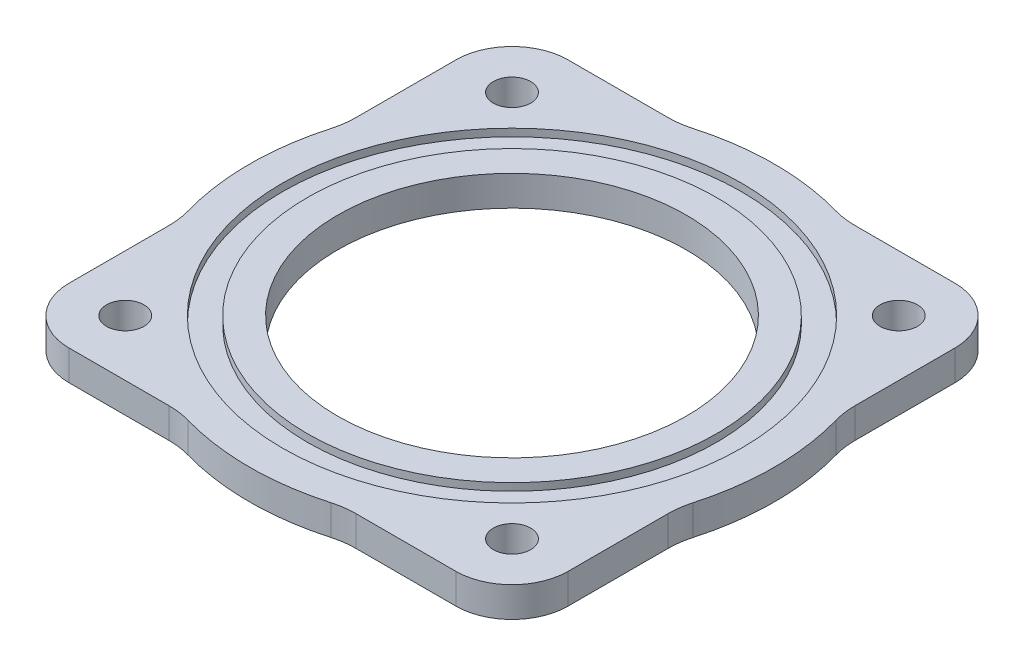
SolidWorks part; units mm, degrees
ref_plane "Front Plane" through (0, 0, 0) normal (0, 0, 1) x (1, 0, 0)
ref_plane "Top Plane" through (0, 0, 0) normal (0, 1, 0) x (1, 0, 0)
ref_plane "Right Plane" through (0, 0, 0) normal (1, 0, 0) x (0, 0, -1)
sketch "Sketch1" plane through (0, 0, 0) normal (0, 1, 0) x (1, 0, 0)
  line L0 (0, 43.6291) -> (0, 56.3563)
  line L1 (7.1437, 0) -> (19.8709, 0)
  line L2 (0, 7.1437) -> (0, 19.8709)
  line L3 (7.1437, 63.5) -> (19.8709, 63.5)
  line L4 (63.5, 7.1437) -> (63.5, 19.8709)
  line L5 (43.6291, 63.5) -> (56.3563, 63.5)
  line L6 (63.5, 43.6291) -> (63.5, 56.3563)
  line L7 (43.6291, 0) -> (56.3563, 0)
  circle A0 centre (31.75, 31.75) radius 22.1742
  circle A1 centre (56.3563, 56.3563) radius 2.3812
  circle A2 centre (56.3563, 7.1437) radius 2.3812
  circle A3 centre (7.1437, 7.1437) radius 2.3812
  circle A4 centre (7.1437, 56.3563) radius 2.3812
  arc A7 (7.1437, 63.5) -> (0, 56.3563) centre (7.1437, 56.3563) ccw
  arc A8 (56.3563, 0) -> (63.5, 7.1437) centre (56.3563, 7.1437) ccw
  arc A9 (0, 7.1437) -> (7.1437, 0) centre (7.1437, 7.1437) ccw
  arc A10 (63.5, 56.3563) -> (56.3563, 63.5) centre (56.3563, 56.3563) ccw
  arc A11 (-0.3851, 40.8585) -> (-0.3851, 22.6415) centre (31.75, 31.75) ccw
  arc A12 (22.6415, -0.3851) -> (40.8585, -0.3851) centre (31.75, 31.75) ccw
  arc A13 (40.8585, 63.8851) -> (22.6415, 63.8851) centre (31.75, 31.75) ccw
  arc A14 (63.8851, 22.6415) -> (63.8851, 40.8585) centre (31.75, 31.75) ccw
  arc A15 (63.8851, 40.8585) -> (63.5, 43.6291) centre (73.66, 43.6291) cw
  arc A16 (63.5, 19.8709) -> (63.8851, 22.6415) centre (73.66, 19.8709) cw
  arc A17 (40.8585, -0.3851) -> (43.6291, 0) centre (43.6291, -10.16) cw
  arc A18 (22.6415, -0.3851) -> (19.8709, 0) centre (19.8709, -10.16) ccw
  arc A19 (0, 19.8709) -> (-0.3851, 22.6415) centre (-10.16, 19.8709) ccw
  arc A20 (-0.3851, 40.8585) -> (0, 43.6291) centre (-10.16, 43.6291) ccw
  arc A21 (22.6415, 63.8851) -> (19.8709, 63.5) centre (19.8709, 73.66) cw
  arc A22 (43.6291, 63.5) -> (40.8585, 63.8851) centre (43.6291, 73.66) cw
  point P16 (63.5, 42.1213)
  point P31 (63.5, 21.3787)
  point P34 (42.1213, 0)
  point P41 (0, 42.1213)
  point P46 (42.1213, 63.5)
  point P47 (0, 0)
  dimension "D3" = 44.3484
  dimension "D6" = 4.7625
  dimension "D7" = 4.7625
  dimension "D8" = 4.7625
  dimension "D9" = 4.7625
  dimension "D10" = 7.1437
  dimension "D11" = 7.1437
  dimension "D12" = 7.1437
  dimension "D13" = 7.1437
  dimension "D14" = 7.1437
  dimension "D15" = 7.1437
  dimension "D16" = 7.1437
  dimension "D17" = 7.1437
  dimension "D18" = 49.2125
  dimension "D2" = 10.16
  dimension "D19" = 11.2268
  dimension "D4" = 31.75
  dimension "D5" = 31.75
extrude "Boss-Extrude1" add sketch "Sketch1" against normal blind 3.8354
sketch "Sketch2" plane through (0, 0, 0) normal (0, 1, 0) x (1, 0, 0)
  circle A0 centre (31.75, 31.75) radius 26.035
  circle A1 centre (31.75, 31.75) radius 29.21
  dimension "D1" = 52.07
  dimension "D2" = 58.42
extrude "Cut-Extrude1" cut sketch "Sketch2" against normal blind 0.9525
